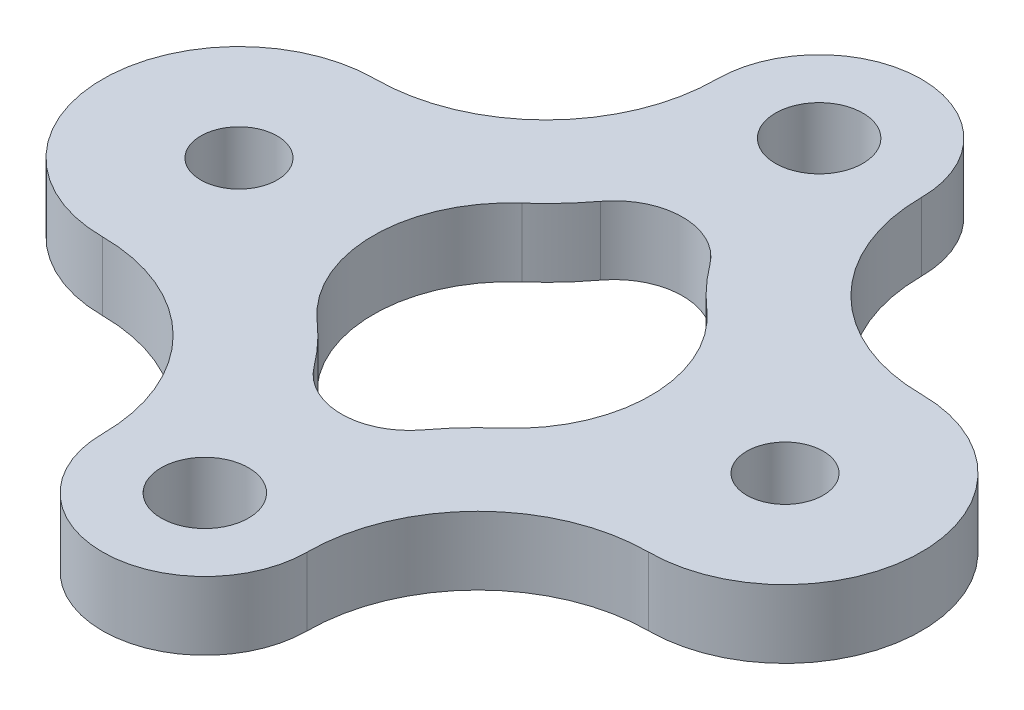
SolidWorks part; units mm, degrees
ref_plane "Front Plane" through (0, 0, 0) normal (0, 0, 1) x (1, 0, 0)
ref_plane "Top Plane" through (0, 0, 0) normal (0, 1, 0) x (1, 0, 0)
ref_plane "Right Plane" through (0, 0, 0) normal (1, 0, 0) x (0, 0, -1)
sketch "Sketch1" plane through (0, 0, 0) normal (0, 1, 0) x (1, 0, 0)
  arc A0 (4.7625, -4.7625) -> (-4.7625, -4.7625) centre (0, -4.7625) ccw
  arc A1 (-12.7, -12.7) -> (-12.7, -25.4) centre (-12.7, -19.05) ccw
  arc A2 (-4.7625, -33.3375) -> (4.7625, -33.3375) centre (0, -33.3375) ccw
  arc A3 (12.7, -12.7) -> (12.7, -25.4) centre (12.7, -19.05) cw
  arc A4 (-12.7, -25.4) -> (-4.7625, -33.3375) centre (-12.7, -33.3375) cw
  arc A5 (4.7625, -33.3375) -> (12.7, -25.4) centre (12.7, -33.3375) cw
  arc A6 (4.7625, -4.7625) -> (12.7, -12.7) centre (12.7, -4.7625) ccw
  arc A7 (-12.7, -12.7) -> (-4.7625, -4.7625) centre (-12.7, -4.7625) ccw
  point P0 (12.7, -19.05)
  point P1 (0, -4.7625)
  point P2 (-12.7, -19.05)
  point P3 (0, -33.3375)
  point P26 (9.372, -32.9445)
  point P27 (0, 0)
  dimension "D1" = 12.7
  dimension "D2" = 9.525
extrude "Boss-Extrude1" add sketch "Sketch1" along normal blind 3.1753
sketch "Sketch2" plane through (0, 3.1753, 0) normal (0, 1, 0) x (1, 0, 0)
  circle A0 centre (0, -4.7625) radius 2.032
  circle A1 centre (12.7, -19.05) radius 1.778
  circle A2 centre (0, -33.3375) radius 2.032
  circle A3 centre (-12.7, -19.05) radius 1.778
  point P9 (-12.7, -19.05)
  point P11 (12.7, -19.05)
  point P13 (0, -33.3375)
  dimension "D1" = 4.064
  dimension "D2" = 3.556
extrude "Cut-Extrude1" cut sketch "Sketch2" against normal through all
sketch "Sketch3" plane through (0, 3.1753, 0) normal (0, 1, 0) x (1, 0, 0)
  arc A16 (-4.2997, -14.2875) -> (-4.2997, -23.8125) centre (-0.0996, -19.05) ccw
  arc A17 (4.2997, -14.2875) -> (4.2997, -23.8125) centre (0.0996, -19.05) cw
  arc A18 (-2.54, -12.3825) -> (2.54, -12.3825) centre (0, -14.2875) cw
  arc A19 (-2.54, -25.7175) -> (2.54, -25.7175) centre (0, -23.8125) ccw
  arc A24 (12.7, -20.6375) -> (0, -33.3375) centre (12.7, -33.3375) ccw
  arc A25 (12.7, -20.6375) -> (12.7, -17.4625) centre (12.7, -19.05) ccw
  arc A26 (0, -4.7625) -> (12.7, -17.4625) centre (12.7, -4.7625) ccw
  arc A27 (-12.7, -17.4625) -> (0, -4.7625) centre (-12.7, -4.7625) ccw
  arc A28 (-12.7, -17.4625) -> (-12.7, -20.6375) centre (-12.7, -19.05) ccw
  arc A29 (0, -33.3375) -> (-12.7, -20.6375) centre (-12.7, -33.3375) ccw
  arc A30 (4.2997, -23.8125) -> (2.54, -25.7175) centre (12.7, -33.3375) ccw
  arc A32 (2.54, -12.3825) -> (4.2997, -14.2875) centre (12.7, -4.7625) ccw
  arc A33 (-4.2997, -14.2875) -> (-2.54, -12.3825) centre (-12.7, -4.7625) ccw
  arc A35 (-2.54, -25.7175) -> (-4.2997, -23.8125) centre (-12.7, -33.3375) ccw
  dimension "D2" = 6.35
  dimension "D3" = 3.175
  dimension "D1" = 4.7625
extrude "Cut-Extrude2" cut sketch "Sketch3" against normal through all
